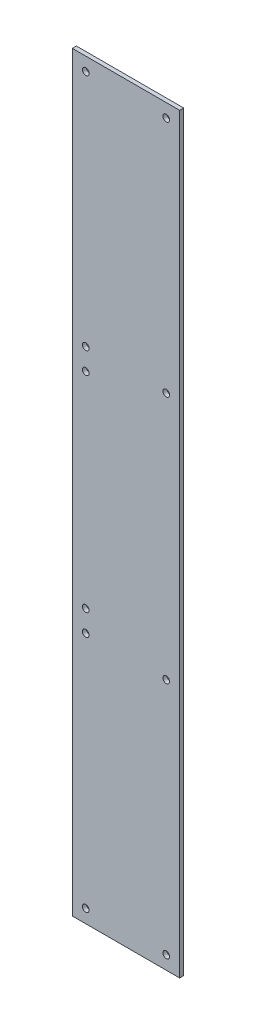
SolidWorks part; units mm, degrees
material "Acrylic (Medium-high impact)"
ref_plane "Front Plane" through (0, 0, 0) normal (0, 0, 1) x (1, 0, 0)
ref_plane "Top Plane" through (0, 0, 0) normal (0, 1, 0) x (1, 0, 0)
ref_plane "Right Plane" through (0, 0, 0) normal (1, 0, 0) x (0, 0, -1)
sketch "Sketch1" plane through (0, 0, 0) normal (0, 0, 1) x (1, 0, 0)
  line L1 (-34.359, 84.1026) -> (45.641, 84.1026)
  line L2 (-34.359, 84.1026) -> (-34.359, -475.8974)
  line L3 (-34.359, -475.8974) -> (45.641, -475.8974)
  line L4 (45.641, 84.1026) -> (45.641, -475.8974)
  dimension "D1" = 80
  dimension "D2" = 560
extrude "Boss-Extrude1" add sketch "Sketch1" along normal blind 3
sketch "Sketch2" plane through (0, 0, 3) normal (0, 0, 1) x (1, 0, 0)
  line L0 (45.641, 84.1026) -> (-34.359, 84.1026) construction
  line L1 (-34.359, 84.1026) -> (-34.359, -475.8974) construction
  line L2 (45.641, -475.8974) -> (45.641, 84.1026) construction
  line L3 (-34.359, -475.8974) -> (45.641, -475.8974) construction
  circle A0 centre (-24.359, 74.1026) radius 2.5
  circle A1 centre (35.641, 74.1026) radius 2.5
  circle A2 centre (-24.359, -465.8974) radius 2.5
  circle A3 centre (35.641, -465.8974) radius 2.5
  circle A6 centre (-24.359, -103.3974) radius 2.5
  circle A7 centre (-24.359, -288.3974) radius 2.5
  circle A8 centre (-24.359, -272.3974) radius 2.5
  circle A9 centre (-24.359, -119.3974) radius 2.5
  circle A10 centre (35.641, -103.3974) radius 2.5
  circle A11 centre (35.641, -288.3974) radius 2.5
  point P18 (35.641, -100.8974)
  point P24 (-24.359, -285.8974)
  point P27 (-24.359, -263.095)
  point P30 (-24.359, -128.4608)
  point P32 (35.641, -285.8974)
  dimension "D1" = 5
  dimension "D3" = 10
  dimension "D4" = 10
  dimension "D6" = 5
  dimension "D7" = 10
  dimension "D8" = 10
  dimension "D9" = 10
  dimension "D10" = 10
  dimension "D13" = 10
  dimension "D14" = 10
  dimension "D15" = 177.5
  dimension "D18" = 185
  dimension "D19" = 177.5
  dimension "D11" = 10
  dimension "D12" = 10
  dimension "D21" = 10
  dimension "D22" = 10
  dimension "D2" = 10
  dimension "D5" = 10
  dimension "D16" = 16
  dimension "D17" = 16
  dimension "D20" = 177.5
extrude "Cut-Extrude1" cut sketch "Sketch2" against normal through all both and the other way through all
